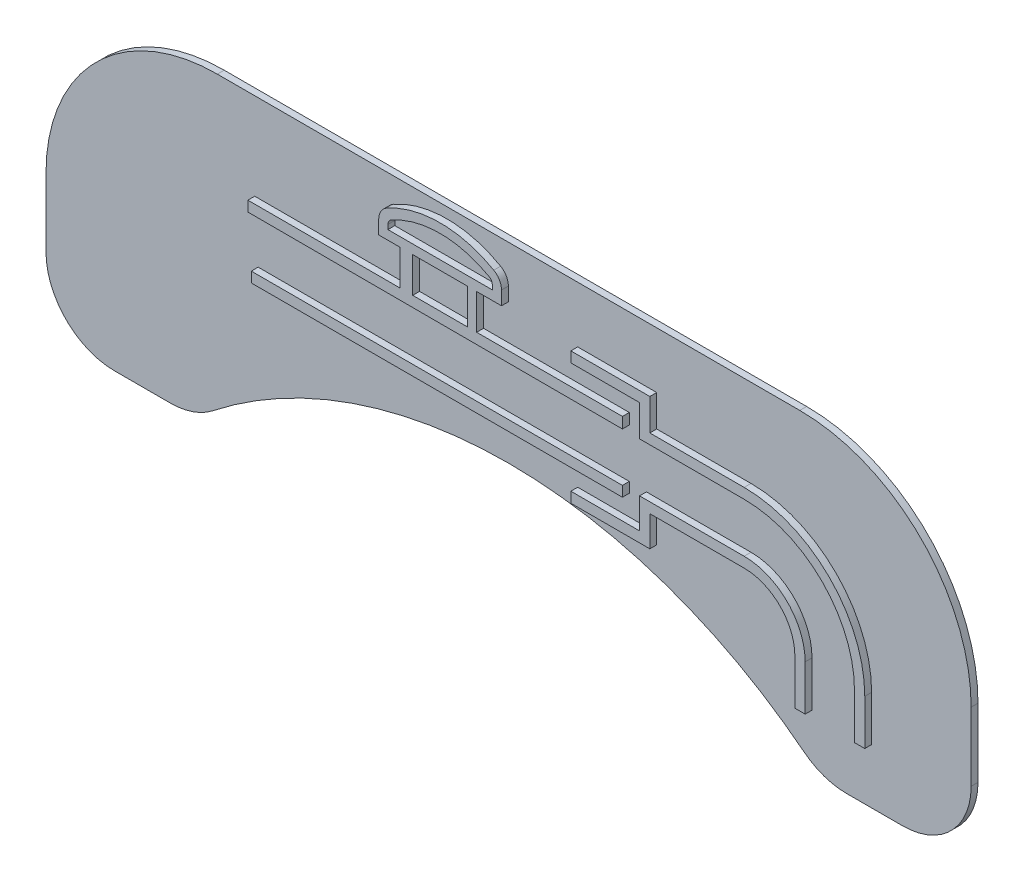
SolidWorks part; units mm, degrees
ref_plane "Plan de face" through (0, 0, 0) normal (0, 0, 1) x (1, 0, 0)
ref_plane "Plan de dessus" through (0, 0, 0) normal (0, 1, 0) x (1, 0, 0)
ref_plane "Plan de droite" through (0, 0, 0) normal (1, 0, 0) x (0, 0, -1)
sketch "Esquisse1" plane through (0, 0, 0) normal (0, 0, 1) x (1, 0, 0)
  line L6 (-27.5, -3.1713) -> (-27.5, -37.8315)
  line L7 (-27.5, -6.0014) -> (-27.5, -8.0014)
  line L9 (-0.5, -0.5014) -> (-0.5, -40.5014)
  line L10 (-0.5, -6.0014) -> (-0.5, -8.0014)
  line L11 (-25.5, -10.0014) -> (-23.8651, -10.0014)
  line L12 (-22.5, -1.0014) -> (0, -1.0014)
  line L13 (-22.5, -1.0014) -> (-5.5, -1.0014)
  line L14 (-4.1349, -10.0014) -> (-2.5, -10.0014)
  arc A0 (-25.5, -10.0014) -> (-27.5, -8.0014) centre (-25.5, -8.0014) cw
  arc A1 (-22.6281, -9.573) -> (-23.8651, -10.0014) centre (-23.8651, -8.0014) cw
  arc A2 (-15.2976, -6.6451) -> (-12.7024, -6.6451) centre (-14, -20.5346) ccw
  arc A3 (-5.3719, -9.573) -> (-22.6281, -9.573) centre (-14, -20.5346) ccw
  arc A4 (-27.5, -6.0014) -> (-22.5, -1.0014) centre (-22.5, -6.0014) cw
  arc A5 (-0.5, -6.0014) -> (-5.5, -1.0014) centre (-5.5, -6.0014) ccw
  arc A6 (-4.1349, -10.0014) -> (-5.3719, -9.573) centre (-4.1349, -8.0014) cw
  arc A7 (-2.5, -10.0014) -> (-0.5, -8.0014) centre (-2.5, -8.0014) ccw
  dimension "D5" = 5
  dimension "D7" = 2
  dimension "D6" = 9
  dimension "D1" = 1
  dimension "D2" = 0.5
  dimension "D3" = 0.5
  dimension "D4" = 0.5
extrude "Extrusion1" add sketch "Esquisse1" along normal blind 0.2
sketch "Esquisse2" plane through (0, 0, 0.2) normal (0, 0, 1) x (1, 0, 0)
  line L0 (-14.7303, -2.5107) -> (-14.006, -2.5107)
  line L1 (-16.9658, -3.5414) -> (-16.9658, -2.5107)
  line L2 (-14.7303, -3.5414) -> (-14.7303, -2.5107)
  line L3 (-16.597, -2.5107) -> (-14.9991, -2.5107)
  line L4 (-16.9658, -3.5414) -> (-21.4084, -3.5414)
  line L5 (-16.597, -3.5414) -> (-14.9991, -3.5414)
  line L6 (-21.3084, -5.2843) -> (-21.3084, -5.5843)
  line L7 (-14.9991, -3.5414) -> (-14.9991, -2.5107)
  line L8 (-16.597, -3.5414) -> (-16.597, -2.5107)
  line L9 (-17.59, -2.5107) -> (-16.9658, -2.5107)
  line L10 (-14.006, -2.5107) -> (-14.006, -2.1115)
  line L11 (-17.59, -2.5107) -> (-17.59, -2.1115)
  line L12 (-17.3212, -2.2419) -> (-14.2748, -2.2419)
  line L13 (-14.2748, -2.2419) -> (-14.2748, -2.1115)
  line L14 (-17.3212, -2.2419) -> (-17.3212, -2.1115)
  line L15 (-21.3084, -5.2843) -> (-10.4772, -5.2843)
  line L16 (-21.3084, -5.5843) -> (-10.4772, -5.5843)
  line L17 (-10.4772, -5.2843) -> (-10.4772, -5.5843)
  line L18 (-21.4084, -3.5414) -> (-21.4084, -3.8414)
  line L19 (-14.7303, -3.5414) -> (-10.4772, -3.5414)
  line L20 (-21.4084, -3.8414) -> (-10.4772, -3.8592)
  line L21 (-10.4772, -3.5414) -> (-10.4772, -3.8592)
  line L23 (-11.983, -2.9414) -> (-11.983, -2.6375)
  line L24 (-11.983, -2.9414) -> (-9.9772, -2.9414)
  line L25 (-11.983, -2.6375) -> (-9.6772, -2.6375)
  line L26 (-9.9772, -2.9414) -> (-9.9772, -3.8592)
  line L27 (-5.4448, -7.0792) -> (-5.4448, -8.3997)
  line L28 (-9.9772, -6.1843) -> (-9.9772, -5.2992)
  line L29 (-11.983, -6.4883) -> (-9.6772, -6.4883)
  line L30 (-11.983, -6.1843) -> (-9.9772, -6.1843)
  line L31 (-11.983, -6.1843) -> (-11.983, -6.4883)
  line L32 (-9.9772, -3.8592) -> (-6.9248, -3.8592)
  line L33 (-9.9772, -5.2992) -> (-6.9248, -5.2992)
  line L34 (-9.6772, -2.6375) -> (-9.6772, -3.5592)
  line L35 (-9.6772, -3.5592) -> (-6.9248, -3.5592)
  line L37 (-9.6772, -5.5992) -> (-6.9248, -5.5992)
  line L38 (-9.6772, -6.4883) -> (-9.6772, -5.5992)
  line L39 (-4.4248, -9.2087) -> (-4.4248, -7.0792) construction
  line L41 (-5.4448, -8.3997) -> (-5.1448, -8.3997)
  line L42 (-5.1448, -8.3997) -> (-5.1448, -7.0792)
  line L43 (-3.7048, -7.0792) -> (-3.7048, -8.3997)
  line L44 (-3.7048, -8.3997) -> (-3.4048, -8.3997)
  line L45 (-3.4048, -8.3997) -> (-3.4048, -7.0792)
  arc A0 (-14.232, -1.7223) -> (-14.006, -2.1115) centre (-14.454, -2.1115) cw
  arc A1 (-17.59, -2.1115) -> (-17.364, -1.7223) centre (-17.142, -2.1115) cw
  arc A2 (-14.3652, -1.9558) -> (-14.2748, -2.1115) centre (-14.454, -2.1115) cw
  arc A3 (-17.2308, -1.9558) -> (-14.3652, -1.9558) centre (-15.798, -4.4674) cw
  arc A4 (-17.3212, -2.1115) -> (-17.2308, -1.9558) centre (-17.142, -2.1115) cw
  arc A5 (-17.364, -1.7223) -> (-14.232, -1.7223) centre (-15.798, -4.4674) cw
  arc A6 (-6.9248, -4.5792) -> (-4.4248, -7.0792) centre (-6.9248, -7.0792) cw construction
  arc A7 (-6.9248, -5.2992) -> (-5.1448, -7.0792) centre (-6.9248, -7.0792) cw
  arc A8 (-6.9248, -3.8592) -> (-3.7048, -7.0792) centre (-6.9248, -7.0792) cw
  arc A9 (-6.9248, -3.5592) -> (-3.4048, -7.0792) centre (-6.9248, -7.0792) cw
  arc A10 (-6.9248, -5.5992) -> (-5.4448, -7.0792) centre (-6.9248, -7.0792) cw
  dimension "D4" = 2.5
  dimension "D1" = 0.6
  dimension "D2" = 0.5
  dimension "D9" = 0.6
extrude "Extrusion2" add sketch "Esquisse2" along normal blind 0.2
